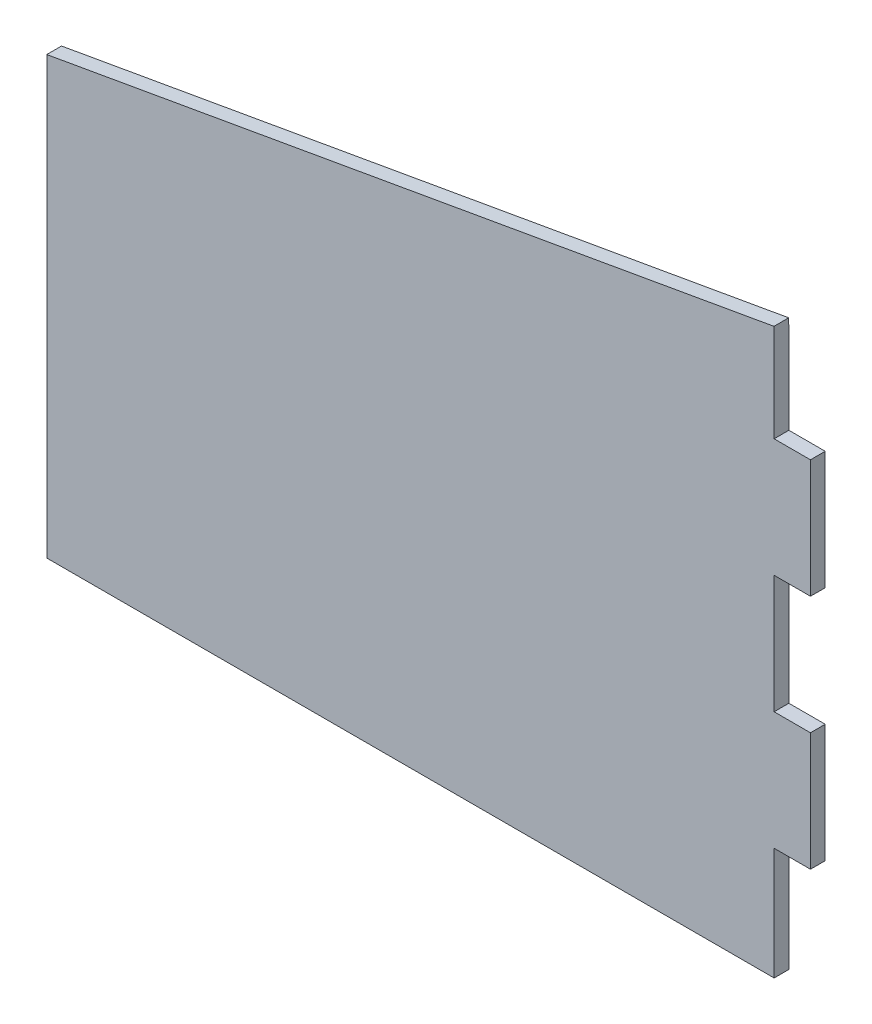
SolidWorks part; units mm, degrees
ref_plane "Front Plane" through (0, 0, 0) normal (0, 0, 1) x (1, 0, 0)
ref_plane "Top Plane" through (0, 0, 0) normal (0, 1, 0) x (1, 0, 0)
ref_plane "Right Plane" through (0, 0, 0) normal (1, 0, 0) x (0, 0, -1)
sketch "Sketch1" plane through (0, 0, 0) normal (0, 0, 1) x (1, 0, 0)
  line L0 (-0.1027, -24.5069) -> (-500.3851, -112.7201)
  line L1 (-500.3851, -112.7201) -> (-500.3851, -412.7201)
  line L2 (-500.3851, -412.7201) -> (0, -412.7201)
  line L3 (0, -412.7201) -> (0, -335.4278)
  line L4 (0, -335.4278) -> (25, -335.4278)
  line L5 (25, -335.4278) -> (25, -254.1108)
  line L6 (0, -254.1108) -> (0, -172.7939)
  line L7 (0, -172.7939) -> (25, -172.7939)
  line L8 (0, -254.1108) -> (25, -254.1108)
  line L9 (0, -91.4769) -> (25, -91.4769)
  line L10 (25, -172.7939) -> (25, -91.4769)
  line L11 (0, -91.4769) -> (-0.1027, -24.5069)
  point P10 (0, 0)
  dimension "D1" = 300
  dimension "D2" = 25
extrude "Boss-Extrude1" add sketch "Sketch1" against normal blind 10.16 from vertex
